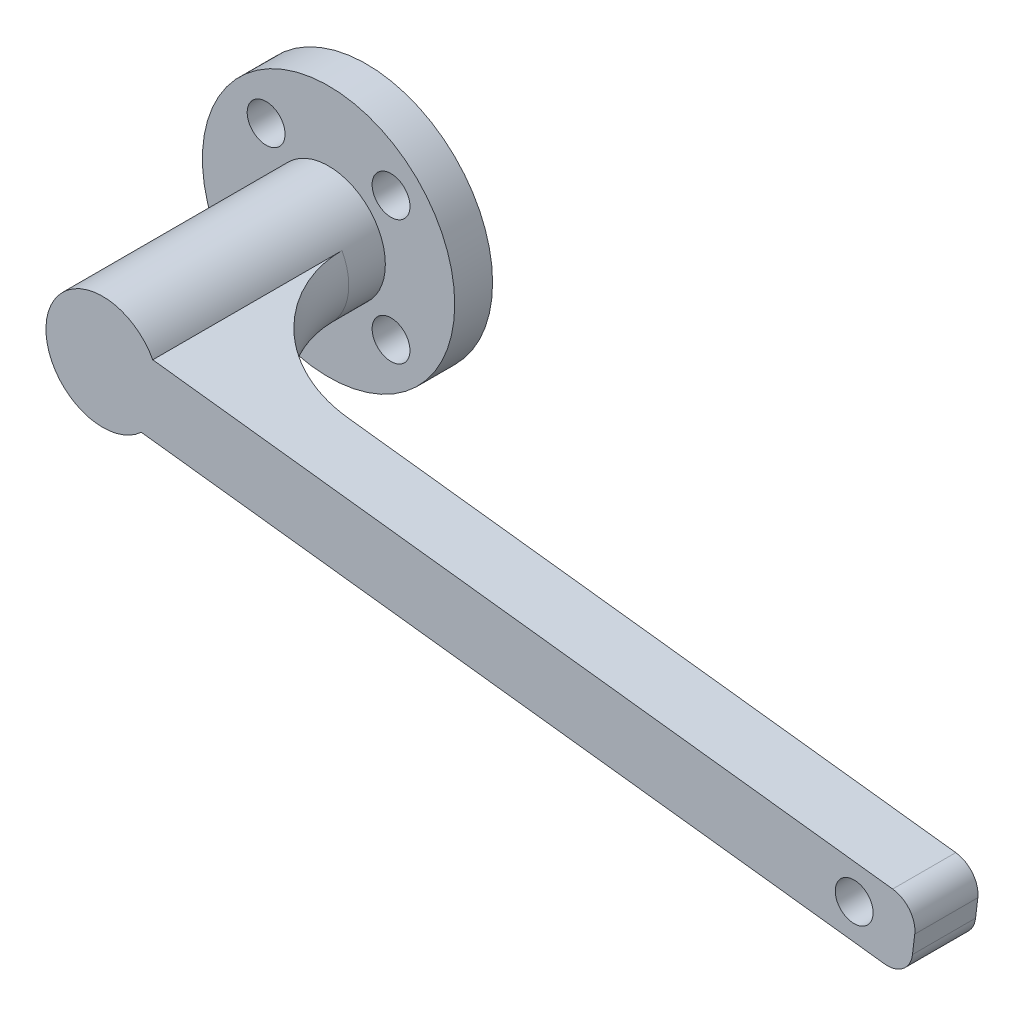
SolidWorks part; units mm, degrees
ref_plane "前视基准面" through (0, 0, 0) normal (0, 0, 1) x (1, 0, 0)
ref_plane "上视基准面" through (0, 0, 0) normal (0, 1, 0) x (1, 0, 0)
ref_plane "右视基准面" through (0, 0, 0) normal (1, 0, 0) x (0, 0, -1)
sketch "草图1" plane through (0, 0, 0) normal (0, 0, 1) x (1, 0, 0)
  circle A0 centre (0, 0) radius 10
  dimension "D1" = 20
extrude "凸台-拉伸1" add sketch "草图1" along normal blind 3
sketch "草图2" plane through (0, 0, 3) normal (0, 0, 1) x (1, 0, 0)
  line L1 (4.95, -4.95) -> (-4.95, -4.95)
  line L2 (4.95, -4.95) -> (4.95, 4.95)
  line L3 (4.95, 4.95) -> (-4.95, 4.95)
  line L4 (-4.95, -4.95) -> (-4.95, 4.95)
  line L5 (4.95, -4.95) -> (-4.95, 4.95) construction
  line L6 (4.95, 4.95) -> (-4.95, -4.95) construction
  circle A0 centre (0, 0) radius 1.5
  circle A2 centre (4.95, 4.95) radius 1.5
  circle A3 centre (-4.95, 4.95) radius 1.5
  circle A4 centre (-4.95, -4.95) radius 1.5
  circle A5 centre (4.95, -4.95) radius 1.5
  dimension "D1" = 3
  dimension "D2" = 9.9
  dimension "D4" = 3
  dimension "D3" = 9.9
extrude "切除-拉伸1" cut sketch "草图2" against normal through all contours L3 A3 L4 | L4 A3 L3 | L2 A2 L3 | L3 A2 L2 | L4 A4 L1 | L1 A4 L4 | L1 A5 L2 | L2 A5 L1 | A0
sketch "草图3" plane through (0, 0, 3) normal (0, 0, 1) x (1, 0, 0)
  circle A0 centre (0, 0) radius 4.5
  circle A1 centre (-4.95, 4.95) radius 1.5 construction
  circle A2 centre (0, 0) radius 10
  circle A3 centre (0, 0) radius 10
  circle A4 centre (-4.95, 4.95) radius 1.5
  circle M5 centre (0, 0) radius 1.5
  dimension "D1" = 0
  dimension "D2" = 9
extrude "凸台-拉伸2" add sketch "草图3" along normal blind 12.9 contours A0 M5
sketch "草图4" plane through (0, 0, 0) normal (0, 0, -1) x (-1, 0, 0)
  circle A0 centre (0, 0) radius 1.5 construction
  circle A3 centre (0, 0) radius 1.5
extrude "凸台-拉伸4" add sketch "草图4" against normal up to surface (15.9 mm away) up to face at (1.5, 0, 15.9)
sketch "草图5" plane through (0, 0, 15.9) normal (0, 0, 1) x (1, 0, 0)
  line L0 (-0.2722, -0.1379) -> (64.2692, -7.8452) construction
  line L1 (64.5953, -5.1146) -> (63.9431, -10.5758)
  line L2 (63.9431, -10.5758) -> (-0.5983, -2.8685)
  line L3 (-0.5983, -2.8685) -> (0.0539, 2.5927)
  line L4 (64.5953, -5.1146) -> (0.0539, 2.5927)
  dimension "D1" = 65
  dimension "D2" = 2.75
extrude "凸台-拉伸5" add sketch "草图5" along normal blind 5
sketch "草图6" plane through (0, 0, 20.9) normal (0, 0, 1) x (1, 0, 0)
  line L0 (64.2692, -7.8452) -> (59.5564, -7.2824) construction
  line L1 (63.9431, -10.5758) -> (64.5953, -5.1146) construction
  line L2 (64.5953, -5.1146) -> (0.0539, 2.5927) construction
  circle A0 centre (59.5564, -7.2824) radius 1.5
  circle A1 centre (0, 0) radius 4.5 construction
  dimension "D1" = 3
  dimension "D2" = 60
extrude "切除-拉伸2" cut sketch "草图6" against normal through all
sketch "草图7" plane through (0, 0, 15.9) normal (0, 0, 1) x (1, 0, 0)
  line L3 (0.0539, 2.5927) -> (3.9664, 2.1255)
  line L4 (3.0544, -3.3047) -> (-0.5983, -2.8685)
  line L5 (-0.5983, -2.8685) -> (0.0539, 2.5927)
  line L6 (0.0539, 2.5927) -> (3.9664, 2.1255)
  line L7 (3.0544, -3.3047) -> (-0.5983, -2.8685)
  line L8 (-0.5983, -2.8685) -> (0.0539, 2.5927)
  arc A1 (3.9664, 2.1255) -> (3.0544, -3.3047) centre (0, 0) ccw
  arc A2 (3.9664, 2.1255) -> (3.0544, -3.3047) centre (0, 0) ccw
  dimension "D1" = 0
extrude "凸台-拉伸8" add sketch "草图7" along normal blind 5 contours L6 A2 L7 L8
fillet "圆角1" radius 10 1 edges at (4.4378, -0.7454, 15.9)
fillet "圆角2" radius 2 2 edges at (63.9431, -10.5758, 18.4) (64.5953, -5.1146, 18.4)
sketch "草图8" plane through (0, 0, 0) normal (0, 0, -1) x (-1, 0, 0)
  circle A0 centre (0, 0) radius 3.75
  dimension "D1" = 7.5
extrude "切除-拉伸3" cut sketch "草图8" against normal blind 3
